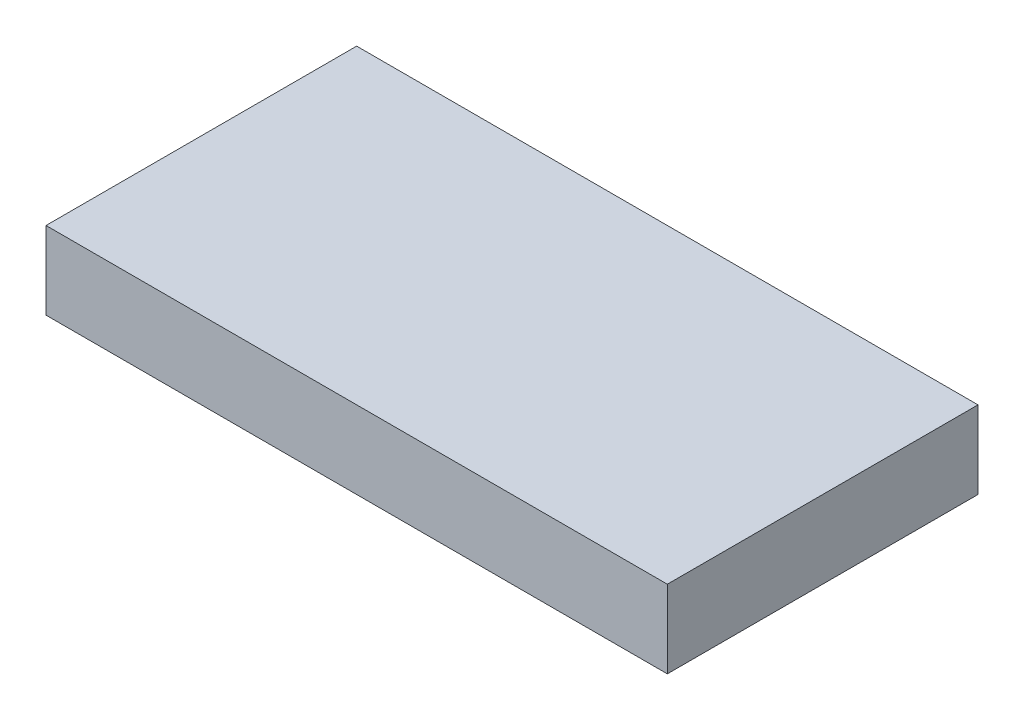
SolidWorks part; units mm, degrees
ref_plane "Front Plane" through (0, 0, 0) normal (0, 0, 1) x (1, 0, 0)
ref_plane "Top Plane" through (0, 0, 0) normal (0, 1, 0) x (1, 0, 0)
ref_plane "Right Plane" through (0, 0, 0) normal (1, 0, 0) x (0, 0, -1)
sketch "Sketch1" plane through (0, 0, 0) normal (0, 1, 0) x (1, 0, 0)
  line L1 (-200, 100) -> (200, 100)
  line L2 (-200, 100) -> (-200, -100)
  line L3 (-200, -100) -> (200, -100)
  line L4 (200, 100) -> (200, -100)
  line L5 (-200, 100) -> (200, -100) construction
  line L6 (-200, -100) -> (200, 100) construction
  point P0 (0, 0)
  dimension "D1" = 400
  dimension "D2" = 200
extrude "Boss-Extrude1" add sketch "Sketch1" along normal blind 50
